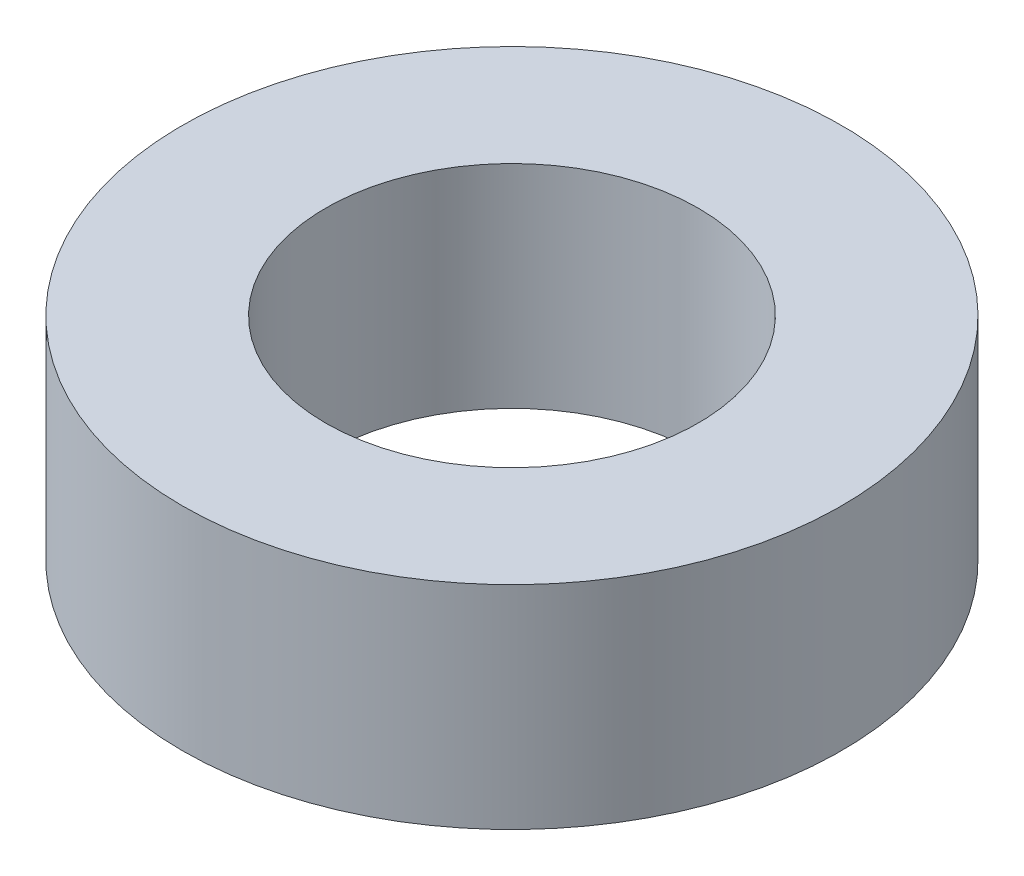
SolidWorks part; units mm, degrees
ref_plane "前视基准面" through (0, 0, 0) normal (0, 0, 1) x (1, 0, 0)
ref_plane "上视基准面" through (0, 0, 0) normal (0, 1, 0) x (1, 0, 0)
ref_plane "右视基准面" through (0, 0, 0) normal (1, 0, 0) x (0, 0, -1)
other "Configuration Table"
sketch "草图1" plane through (0, 0, 0) normal (0, 1, 0) x (1, 0, 0)
  circle A0 centre (0, 0) radius 5.2
  circle A1 centre (0, 0) radius 9.2
  dimension "D1" = 10.4
  dimension "D2" = 4
extrude "凸台-拉伸1" add sketch "草图1" along normal blind 5.92
